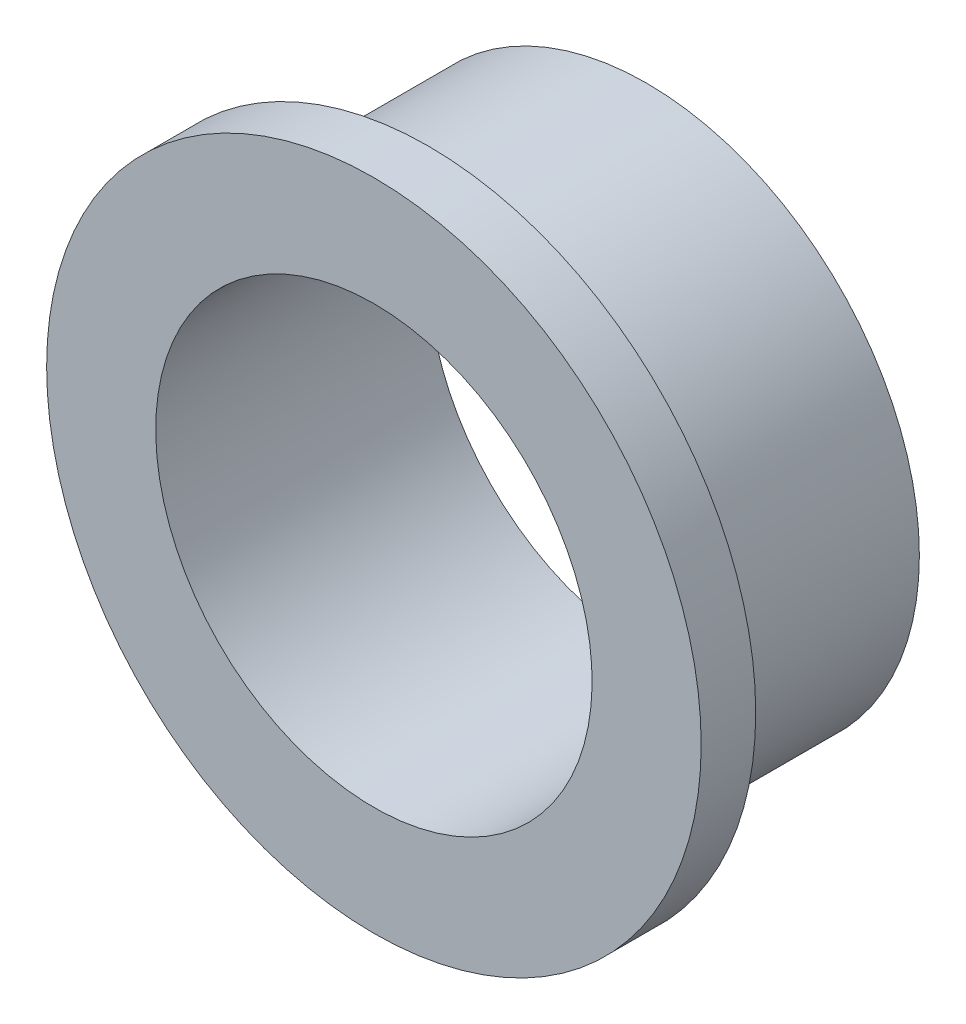
SolidWorks part; units mm, degrees
material "Tin Bearing Bronze"
ref_plane "Front Plane" through (0, 0, 0) normal (0, 0, 1) x (1, 0, 0)
ref_plane "Top Plane" through (0, 0, 0) normal (0, 1, 0) x (1, 0, 0)
ref_plane "Right Plane" through (0, 0, 0) normal (1, 0, 0) x (0, 0, -1)
sketch "Sketch1" plane through (0, 0, 0) normal (1, 0, 0) x (0, 0, -1)
  line L0 (-15.3979, -6.35) -> (-36.4549, -6.35) construction
  line L1 (12.7, -6.35) -> (-12.7, -6.35)
  line L2 (12.7, -6.35) -> (12.7, 6.35)
  line L3 (12.7, 6.35) -> (-12.7, 6.35)
  line L4 (-12.7, -6.35) -> (-12.7, 6.35)
  line L5 (12.7, -6.35) -> (-12.7, 6.35) construction
  line L6 (12.7, 6.35) -> (-12.7, -6.35) construction
  line L7 (12.7, 6.35) -> (-9.525, 6.35)
  line L8 (12.7, 6.35) -> (12.7, 9.525)
  line L9 (12.7, 9.525) -> (-9.525, 9.525)
  line L10 (-9.525, 6.35) -> (-9.525, 9.525)
  line L11 (-12.7, 6.35) -> (-9.525, 6.35)
  line L12 (-12.7, 6.35) -> (-12.7, 12.7)
  line L13 (-12.7, 12.7) -> (-9.525, 12.7)
  line L14 (-9.525, 6.35) -> (-9.525, 12.7)
  line L15 (3.175, 9.525) -> (3.175, 6.35)
  point P0 (0, 0)
  dimension "D1" = 12.7
  dimension "D2" = 25.4
  dimension "D3" = 3.175
  dimension "D4" = 6.35
  dimension "D5" = 22.225
  dimension "D6" = 3.175
  dimension "D7" = 15.875
revolve "Revolve1" add sketch "Sketch1" angle 360 about L0
